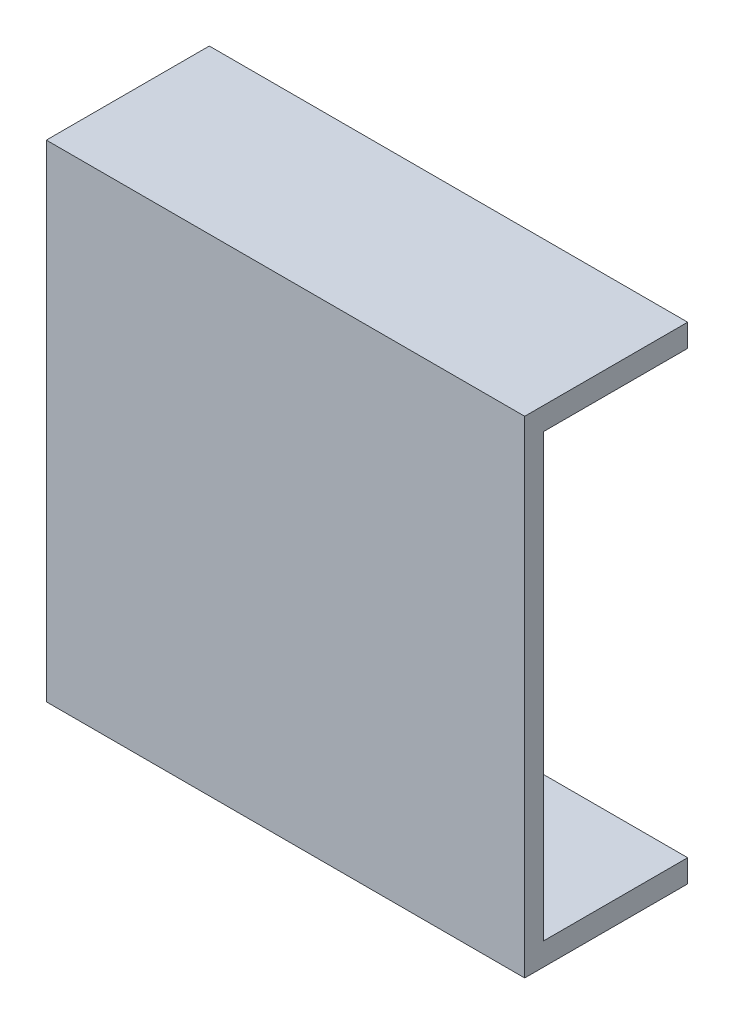
SolidWorks part; units mm, degrees
ref_plane "前视" through (0, 0, 0) normal (0, 0, 1) x (1, 0, 0)
ref_plane "上视" through (0, 0, 0) normal (0, 1, 0) x (1, 0, 0)
ref_plane "右视" through (0, 0, 0) normal (1, 0, 0) x (0, 0, -1)
sketch "草图1" plane through (0, 0, 0) normal (0, 0, 1) x (1, 0, 0)
  line L0 (0, 0) -> (0, 94.429) construction
  line L1 (-147.5, 300) -> (147.5, 300)
  line L2 (-147.5, 300) -> (-147.5, 0)
  line L3 (-147.5, 0) -> (147.5, 0)
  line L4 (147.5, 300) -> (147.5, 0)
  line L5 (-203.17, 70) -> (213.5889, 70) construction
  line L6 (-203.17, 150) -> (228.17, 150) construction
  line L7 (-203.17, 230) -> (213.5889, 230) construction
  line L8 (92.5, -78.7935) -> (92.5, 321.0346) construction
  line L9 (12.5, -78.7935) -> (12.5, 279.3587) construction
  line L10 (-67.5, -78.7935) -> (-67.5, 279.3587) construction
  line L11 (-244.8459, 0) -> (338.6166, 0) construction
  circle A0 centre (92.5, 230) radius 13
  circle A1 centre (92.5, 150) radius 13
  circle A2 centre (92.5, 70) radius 13
  circle A3 centre (12.5, 230) radius 13
  circle A4 centre (-67.5, 230) radius 13
  circle A5 centre (-67.5, 150) radius 13
  circle A6 centre (-67.5, 70) radius 13
  circle A7 centre (12.5, 70) radius 13
  circle A8 centre (12.5, 150) radius 13
  dimension "D9" = 26
  dimension "D10" = 135
  dimension "D1" = 300
  dimension "D2" = 295
  dimension "D3" = 70
  dimension "D4" = 80
  dimension "D5" = 80
  dimension "D6" = 55
  dimension "D7" = 80
  dimension "D8" = 80
extrude "基体-拉伸" add sketch "草图1" along normal blind 11.5
sketch "草图2" plane through (0, 0, 0) normal (0, 0, -1) x (-1, 0, 0)
  line L0 (147.5, 300) -> (147.5, 0) construction
  line L1 (-147.5, 300) -> (147.5, 300)
  line L2 (-147.5, 300) -> (-147.5, 286)
  line L3 (-147.5, 286) -> (147.5, 286)
  line L4 (147.5, 300) -> (147.5, 286)
  line L6 (-147.5, 0) -> (147.5, 0)
  line L7 (-147.5, 0) -> (-147.5, 14)
  line L8 (-147.5, 14) -> (147.5, 14)
  line L9 (147.5, 0) -> (147.5, 14)
  dimension "D1" = 14
  dimension "D2" = 14
extrude "凸台-拉伸1" add sketch "草图2" along normal blind 89
sketch "草图3" plane through (0, 300, 0) normal (0, 1, 0) x (-1, 0, 0)
  line L0 (0, 10.854) -> (0, -103.2512) construction
  line L1 (145.3179, -53.5) -> (-138.666, -53.5) construction
  line L2 (-147.5, 11.5) -> (147.5, 11.5) construction
  line L3 (-147.5, 11.5) -> (-147.5, -89) construction
  circle A0 centre (-27.5, -53.5) radius 13
  circle A1 centre (52.5, -53.5) radius 13
  dimension "D4" = 26
  dimension "D1" = 65
  dimension "D2" = 120
  dimension "D3" = 80
extrude "切除-拉伸1" cut sketch "草图3" against normal through all
sketch "草图4" plane through (0, 0, 0) normal (0, 0, -1) x (-1, 0, 0)
  line L1 (-147.5, 286) -> (147.5, 286)
  line L2 (-147.5, 286) -> (-147.5, 14)
  line L3 (-147.5, 14) -> (147.5, 14)
  line L4 (147.5, 286) -> (147.5, 14)
extrude "凸台-拉伸2" add sketch "草图4" against normal blind 11.5
sketch "草图5" plane through (0, 0, -89) normal (0, 0, -1) x (-1, 0, 0)
  line L1 (-147.5, 300) -> (147.5, 300)
  line L2 (-147.5, 300) -> (-147.5, 286)
  line L3 (-147.5, 286) -> (147.5, 286)
  line L4 (147.5, 300) -> (147.5, 286)
  line L5 (-147.5, 14) -> (147.5, 14)
  line L6 (-147.5, 14) -> (-147.5, 0)
  line L7 (-147.5, 0) -> (147.5, 0)
  line L8 (147.5, 14) -> (147.5, 0)
extrude "凸台-拉伸3" add sketch "草图5" against normal blind 89
